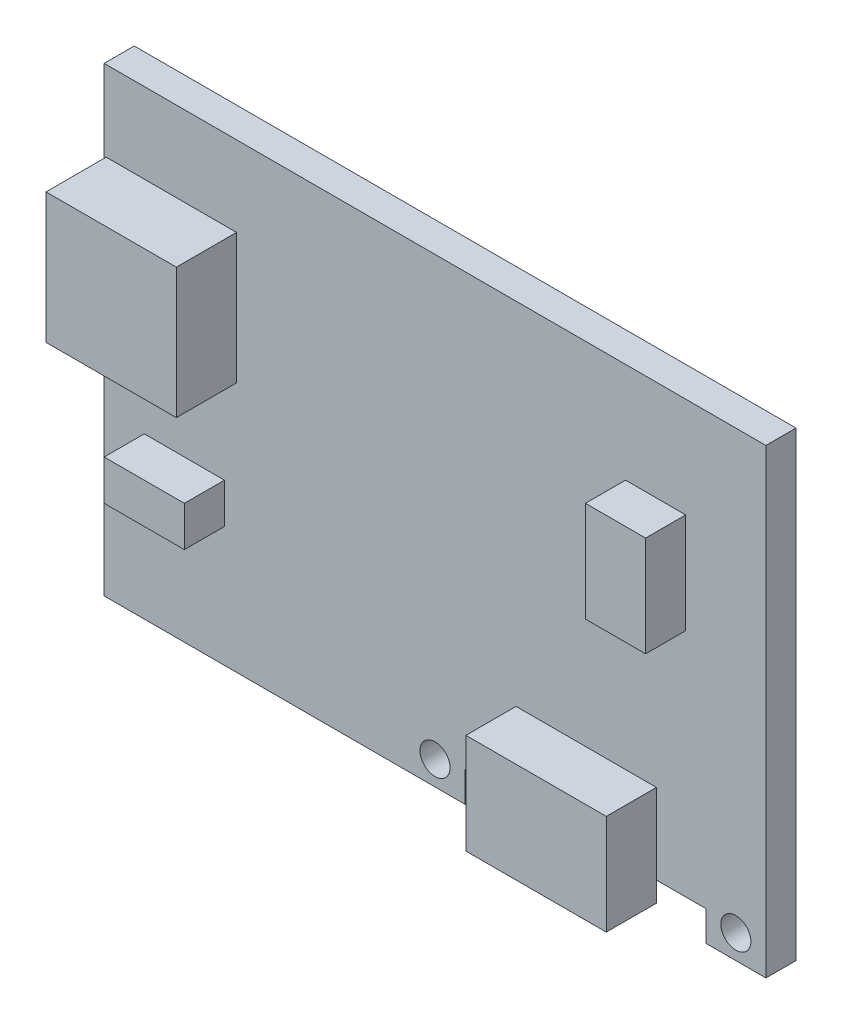
SolidWorks part; units mm, degrees
ref_plane "Front" through (0, 0, 0) normal (0, 0, 1) x (1, 0, 0)
ref_plane "Top" through (0, 0, 0) normal (0, 1, 0) x (1, 0, 0)
ref_plane "Right" through (0, 0, 0) normal (1, 0, 0) x (0, 0, -1)
sketch "草图1" plane through (0, 0, 0) normal (0, 0, 1) x (1, 0, 0)
  line L1 (0, 0) -> (33, 0)
  line L2 (0, 0) -> (0, 23)
  line L3 (0, 23) -> (33, 23)
  line L4 (33, 0) -> (33, 23)
  dimension "D1" = 23
  dimension "D2" = 33
extrude "凸台-拉伸1" add sketch "草图1" along normal blind 1.5
sketch "草图2" plane through (0, 0, 1.5) normal (0, 0, 1) x (1, 0, 0)
  line L0 (0, 0) -> (33, 0) construction
  line L1 (18, 0) -> (30, 0)
  line L2 (18, 0) -> (18, 1.5)
  line L3 (18, 1.5) -> (30, 1.5)
  line L4 (30, 0) -> (30, 1.5)
  line L5 (33, 0) -> (33, 23) construction
  dimension "D1" = 12
  dimension "D2" = 1.5
  dimension "D3" = 3
extrude "切除-拉伸1" cut sketch "草图2" against normal through all
sketch "草图3" plane through (0, 0, 1.5) normal (0, 0, 1) x (1, 0, 0)
  line L0 (30, 1.5) -> (18, 1.5) construction
  line L1 (33, 0) -> (33, 23) construction
  line L2 (18, 1.5) -> (18, 0) construction
  circle A0 centre (31.5, 1.2) radius 0.75
  circle A1 centre (16.5, 1.2) radius 0.75
  dimension "D1" = 0.3
  dimension "D2" = 1.5
  dimension "D3" = 1.5
extrude "切除-拉伸2" cut sketch "草图3" against normal through all
sketch "草图4" plane through (0, 0, 1.5) normal (0, 0, 1) x (1, 0, 0)
  line L0 (0, 23) -> (0, 0) construction
  line L1 (2, 8) -> (6, 8)
  line L2 (2, 8) -> (2, 6)
  line L3 (2, 6) -> (6, 6)
  line L4 (6, 8) -> (6, 6)
  line L5 (0, 0) -> (18, 0) construction
  dimension "D1" = 4
  dimension "D2" = 2
  dimension "D3" = 2
  dimension "D4" = 6
extrude "凸台-拉伸2" add sketch "草图4" along normal blind 2
sketch "草图5" plane through (0, 0, 1.5) normal (0, 0, 1) x (1, 0, 0)
  line L0 (33, 0) -> (33, 23) construction
  line L1 (26, 18) -> (29, 18)
  line L2 (26, 18) -> (26, 13)
  line L3 (26, 13) -> (29, 13)
  line L4 (29, 18) -> (29, 13)
  line L5 (33, 23) -> (0, 23) construction
  dimension "D1" = 5
  dimension "D2" = 3
  dimension "D3" = 4
  dimension "D4" = 5
extrude "凸台-拉伸3" add sketch "草图5" along normal blind 2
sketch "草图6" plane through (0, 0, 1.5) normal (0, 0, 1) x (1, 0, 0)
  line L0 (0, 23) -> (0, 0) construction
  line L1 (0.1, 19) -> (6.6, 19)
  line L2 (0.1, 19) -> (0.1, 12.5)
  line L3 (0.1, 12.5) -> (6.6, 12.5)
  line L4 (6.6, 19) -> (6.6, 12.5)
  line L5 (33, 23) -> (0, 23) construction
  dimension "D1" = 6.5
  dimension "D2" = 6.5
  dimension "D3" = 0.1
  dimension "D4" = 4
extrude "凸台-拉伸4" add sketch "草图6" along normal blind 3
sketch "草图7" plane through (0, 0, 1.5) normal (0, 0, 1) x (1, 0, 0)
  line L0 (0, 0) -> (18, 0) construction
  line L1 (20.5391, 5.5) -> (27.5391, 5.5)
  line L2 (20.5391, 5.5) -> (20.5391, 0.5)
  line L3 (20.5391, 0.5) -> (27.5391, 0.5)
  line L4 (27.5391, 5.5) -> (27.5391, 0.5)
  dimension "D1" = 7
  dimension "D2" = 5
  dimension "D3" = 0.5
extrude "凸台-拉伸5" add sketch "草图7" along normal blind 2.5
